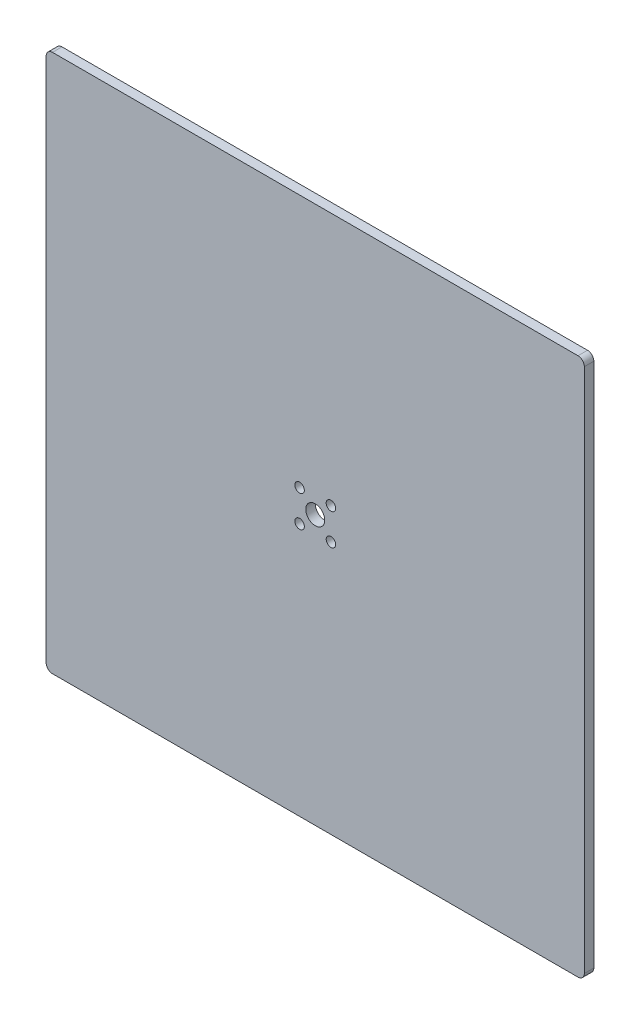
SolidWorks part; units mm, degrees
ref_plane "前视基准面" through (0, 0, 0) normal (0, 0, 1) x (1, 0, 0)
ref_plane "上视基准面" through (0, 0, 0) normal (0, 1, 0) x (1, 0, 0)
ref_plane "右视基准面" through (0, 0, 0) normal (1, 0, 0) x (0, 0, -1)
sketch "草图1" plane through (0, 0, 0) normal (0, 0, 1) x (1, 0, 0)
  line L1 (85, -85) -> (-85, -85)
  line L2 (85, -85) -> (85, 85)
  line L3 (85, 85) -> (-85, 85)
  line L4 (-85, -85) -> (-85, 85)
  line L5 (85, -85) -> (-85, 85) construction
  line L6 (85, 85) -> (-85, -85) construction
  point P0 (0, 0)
  dimension "D1" = 170
  dimension "D2" = 170
extrude "凸台-拉伸1" add sketch "草图1" along normal blind 3
sketch "草图3" plane through (0, 0, 0) normal (0, 0, -1) x (-1, 0, 0)
  line L1 (4.95, -4.95) -> (-4.95, -4.95) construction
  line L2 (4.95, -4.95) -> (4.95, 4.95) construction
  line L3 (4.95, 4.95) -> (-4.95, 4.95) construction
  line L4 (-4.95, -4.95) -> (-4.95, 4.95) construction
  line L5 (4.95, -4.95) -> (-4.95, 4.95) construction
  line L6 (4.95, 4.95) -> (-4.95, -4.95) construction
  circle A0 centre (0, 0) radius 3
  circle A1 centre (4.95, 4.95) radius 1.5
  circle A2 centre (-4.95, 4.95) radius 1.5
  circle A3 centre (-4.95, -4.95) radius 1.5
  circle A4 centre (4.95, -4.95) radius 1.5
  point P0 (0, 0)
  dimension "D1" = 6
  dimension "D2" = 3
  dimension "D3" = 3
  dimension "D4" = 3
  dimension "D5" = 3
  dimension "D6" = 9.9
  dimension "D7" = 9.9
extrude "切除-拉伸1" cut sketch "草图3" against normal through all
fillet "圆角1" radius 2 4 edges at (85, -85, 1.5) (85, 85, 1.5) (-85, -85, 1.5) (-85, 85, 1.5)
